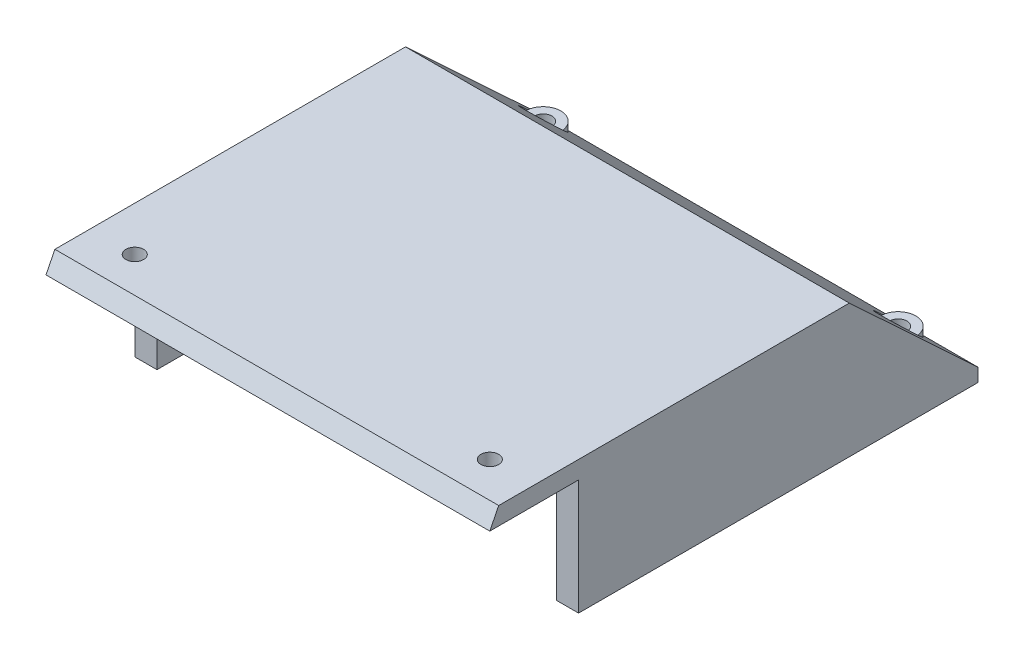
SolidWorks part; units mm, degrees
ref_plane "Front Plane" through (0, 0, 0) normal (0, 0, 1) x (1, 0, 0)
ref_plane "Top Plane" through (0, 0, 0) normal (0, 1, 0) x (1, 0, 0)
ref_plane "Right Plane" through (0, 0, 0) normal (1, 0, 0) x (0, 0, -1)
sketch "Sketch1" plane through (0, 0, 0) normal (0, 1, 0) x (1, 0, 0)
  line L1 (-50, 45) -> (50, 45)
  line L2 (-50, 45) -> (-50, -45)
  line L3 (-50, -45) -> (-45, -45)
  line L4 (50, 45) -> (50, -45)
  line L5 (-50, 45) -> (50, -45) construction
  line L6 (-50, -45) -> (50, 45) construction
  line L9 (45, -45) -> (45, 40)
  line L10 (45, 40) -> (-45, 40)
  line L11 (-45, -45) -> (-45, 40)
  line L12 (45, -45) -> (50, -45)
  point P0 (0, 0)
  dimension "D1" = 100
  dimension "D2" = 90
  dimension "D3" = 5
  dimension "D4" = 5
  dimension "D5" = 5
extrude "Boss-Extrude1" add sketch "Sketch1" along normal blind 3
sketch "Sketch2" plane through (0, 0, 45) normal (0, 0, 1) x (1, 0, 0)
  line L0 (-50, 0) -> (-50, 30) construction
  line L1 (-50, 3) -> (-50, 30)
  line L2 (50, 3) -> (50, 30)
  line L3 (50, 30) -> (-50, 30)
  line L4 (-50, 3) -> (-45, 3)
  line L5 (-45, 3) -> (-45, 23)
  line L6 (50, 3) -> (45, 3)
  line L7 (45, 3) -> (45, 23)
  line L8 (45, 23) -> (-45, 23)
  dimension "D1" = 30
  dimension "D2" = 7
extrude "Boss-Extrude2" add sketch "Sketch2" against normal blind 3
sketch "Sketch3" plane through (0, 0, 45) normal (0, 0, 1) x (1, 0, 0)
  line L0 (50, 30) -> (50, 0) construction
  line L1 (-50, 30) -> (50, 30)
  line L2 (-50, 30) -> (-50, 26)
  line L3 (-50, 26) -> (50, 26)
  line L4 (50, 30) -> (50, 26)
  dimension "D1" = 4
extrude "Boss-Extrude3" add sketch "Sketch3" along normal blind 20
sketch "Sketch4" plane through (50, 0, 0) normal (1, 0, 0) x (0, 0, -1)
  line L0 (-65, 26) -> (-65, 30)
  line L1 (-65, 30) -> (-63, 30)
  line L2 (-42, 30) -> (-65, 30) construction
  line L3 (-63, 30) -> (-65, 26)
  dimension "D1" = 2
extrude "Cut-Extrude1" cut sketch "Sketch4" against normal blind 106
sketch "Sketch5" plane through (0, 0, 42) normal (0, 0, -1) x (-1, 0, 0)
  line L0 (-50, 3) -> (-46, 3)
  line L1 (-50, 3) -> (50, 3) construction
  line L2 (-46, 3) -> (-46, 27)
  line L3 (-46, 27) -> (46, 27)
  line L4 (46, 27) -> (46, 3)
  line L5 (50, 3) -> (45, 3) construction
  line L6 (46, 3) -> (50, 3)
  line L7 (50, 3) -> (50, 30)
  line L8 (50, 30) -> (-50, 30)
  line L9 (-50, 30) -> (-50, 3)
  dimension "D1" = 4
  dimension "D2" = 3
  dimension "D3" = 4
extrude "Boss-Extrude4" add sketch "Sketch5" along normal blind 58
sketch3d "3DSketch1"
  line L0 (-50, 30, -16) -> (50, 30, -16) construction
  line L1 (50, 3, -45) -> (-50, 3, -45) construction
sketch "Sketch6" plane through (0, 24.0497, -22.3911) normal (0, -0.7319, 0.6814) x (-1, 0, 0)
  line L0 (-50, -8.7323) -> (50, -8.7323)
  line L1 (50, -8.7323) -> (-50, -8.7323) construction
  line L2 (50, -8.7323) -> (50, 30.891)
  line L3 (50, 30.891) -> (-50, 30.891)
  line L4 (-50, 30.891) -> (-50, -8.7323)
  dimension "D1" = 0
extrude "Boss-Extrude5" add sketch "Sketch6" along normal blind 3
sketch "Sketch7" plane through (0, 0, -16) normal (0, 0, -1) x (-1, 0, 0)
  line L1 (-50, 25.901) -> (-46, 25.901)
  line L2 (-50, 25.901) -> (-50, 3)
  line L3 (-50, 3) -> (-46, 3)
  line L4 (-46, 25.901) -> (-46, 3)
  line L5 (50, 25.901) -> (46, 25.901)
  line L6 (50, 25.901) -> (50, 3)
  line L7 (50, 3) -> (46, 3)
  line L8 (46, 25.901) -> (46, 3)
extrude "Boss-Extrude6" add sketch "Sketch7" along normal up to next
sketch "Sketch8" plane through (0, 0, 0) normal (0, -1, 0) x (1, 0, 0)
  line L0 (-50, -45) -> (-50, 45) construction
  line L1 (-45, 35) -> (45, 35)
  line L2 (-45, 35) -> (-45, -15)
  line L3 (-45, -15) -> (45, -15)
  line L4 (45, 35) -> (45, -15)
  line L5 (50, 45) -> (50, -45) construction
  line L6 (-50, 45) -> (-45, 45) construction
  dimension "D1" = 50
  dimension "D2" = 5
  dimension "D3" = 5
  dimension "D4" = 10
sketch "Sketch10" plane through (0, 30, 0) normal (0, 1, 0) x (1, 0, 0)
  line L0 (-50, -65) -> (50, -65) construction
  line L1 (50, 16) -> (50, -63) construction
  line L2 (-50, 16) -> (-50, -63) construction
  circle A0 centre (40, -55) radius 2
  circle A1 centre (-40, -55) radius 2
  dimension "D3" = 10
  dimension "D4" = 10
  dimension "D5" = 4
  dimension "D6" = 4
  dimension "D1" = 10
  dimension "D2" = 10
extrude "Cut-Extrude3" cut sketch "Sketch10" against normal blind 10
sketch "Sketch11" plane through (0, 0, 0) normal (0, -1, 0) x (1, 0, 0)
  line L0 (-50, -45) -> (-50, 45) construction
  line L3 (50, -45) -> (-50, -45) construction
  line L4 (50, 45) -> (50, -45) construction
  line L5 (-40, -33) -> (-48.829, -33)
  line L6 (-48.829, -33) -> (-48.829, -41)
  line L7 (-48.829, -41) -> (-40, -41)
  line L8 (40, -33) -> (48.6146, -33)
  line L9 (48.6146, -33) -> (48.6146, -41)
  line L10 (48.6146, -41) -> (40, -41)
  arc A0 (-40, -41) -> (-40, -33) centre (-40, -37) ccw
  arc A1 (40, -33) -> (40, -41) centre (40, -37) ccw
  dimension "D2" = 8
  dimension "D3" = 10
  dimension "D4" = 8
  dimension "D5" = 8
  dimension "D6" = 8
  dimension "D1" = 10
extrude "Boss-Extrude8" add sketch "Sketch11" against normal up to surface (10.0735 mm away)
sketch "Sketch12" plane through (0, 0, 0) normal (0, -1, 0) x (1, 0, 0)
  circle A0 centre (-40, -37) radius 2
  circle A1 centre (40, -37) radius 2
  dimension "D1" = 4
  dimension "D2" = 4
extrude "Cut-Extrude4" cut sketch "Sketch12" against normal through all
sketch "Sketch13" plane through (0, 0, 0) normal (0, -1, 0) x (1, 0, 0)
  line L1 (-45, -33) -> (45, -33)
  line L2 (-45, -33) -> (-45, -40)
  line L3 (-45, -40) -> (45, -40)
  line L4 (45, -33) -> (45, -40)
  dimension "D1" = 90
  dimension "D2" = 7
extrude "Cut-Extrude5" cut sketch "Sketch13" against normal blind 3
sketch "Sketch15" plane through (0, 30, 0) normal (0, 1, 0) x (1, 0, 0)
  circle A0 centre (-40, 37) radius 2
  circle A1 centre (40, 37) radius 2
  circle A2 centre (-40, 37) radius 4
  circle A3 centre (40, 37) radius 4
  dimension "D1" = 8
  dimension "D2" = 8
extrude "Cut-Extrude6" cut sketch "Sketch15" against normal blind 21
sketch "Sketch16" plane through (0, 9, 0) normal (0, 1, 0) x (1, 0, 0)
  circle A0 centre (-40, 37) radius 2
  circle A1 centre (-40, 37) radius 4
  circle A2 centre (40, 37) radius 2
  circle A3 centre (40, 37) radius 4
extrude "Boss-Extrude9" add sketch "Sketch16" along normal blind 1 and the other way blind 3
sketch "Sketch17" plane through (0, 27, 0) normal (0, -1, 0) x (1, 0, 0)
  line L0 (-41.5, 33.7842) -> (41.5, 33.7842)
  line L1 (-38.5, 30.7842) -> (38.5, 30.7842)
  line L2 (-38.5, 30.7842) -> (-38.5, -11.7158)
  line L3 (-38.5, -11.7158) -> (38.5, -11.7158)
  line L4 (38.5, 30.7842) -> (38.5, -11.7158)
  line L5 (-38.5, 30.7842) -> (38.5, -11.7158) construction
  line L6 (-38.5, -11.7158) -> (38.5, 30.7842) construction
  line L7 (41.5, 33.7842) -> (41.5, -14.7158)
  line L8 (-41.5, -14.7158) -> (41.5, -14.7158)
  line L9 (-41.5, 33.7842) -> (-41.5, -14.7158)
  point P0 (0, 9.5342)
  dimension "D1" = 77
  dimension "D2" = 42.5
  dimension "D3" = 0
  dimension "D4" = 3
extrude "Boss-Extrude10" add sketch "Sketch17" along normal blind 5
sketch "Sketch9" plane through (0, 0, 0) normal (0, -1, 0) x (1, 0, 0)
  line L0 (50, 45) -> (50, -45) construction
  line L1 (-50, -45) -> (50, -45)
  line L2 (-50, -45) -> (-50, -42)
  line L3 (-50, -42) -> (50, -42)
  line L4 (50, -45) -> (50, -42)
  dimension "D1" = 3
